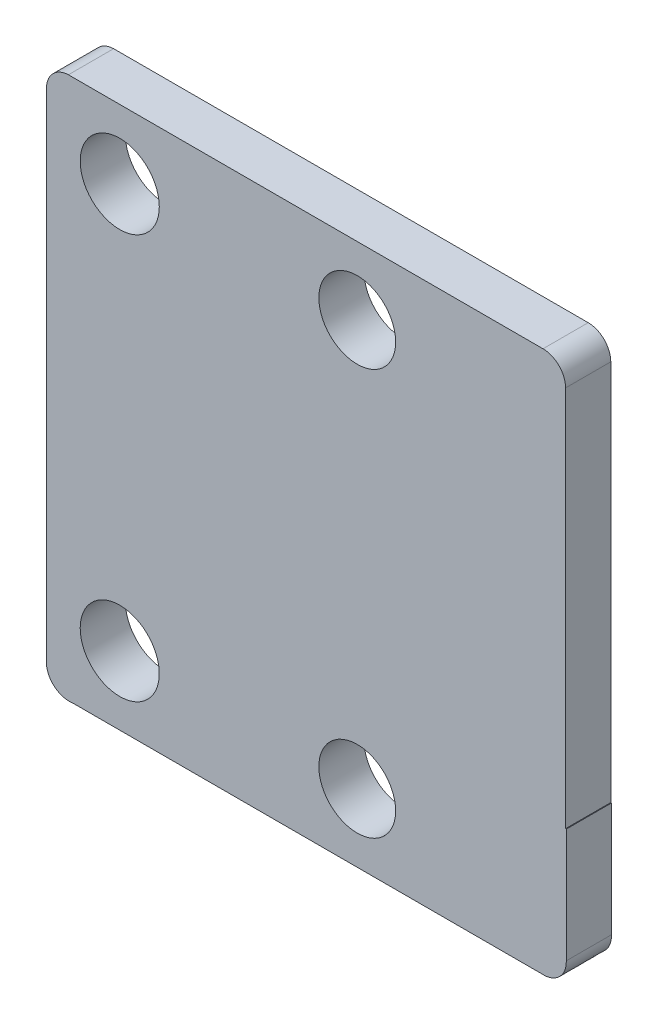
SolidWorks part; units mm, degrees
ref_plane "Front Plane" through (0, 0, 0) normal (0, 0, 1) x (1, 0, 0)
ref_plane "Top Plane" through (0, 0, 0) normal (0, 1, 0) x (1, 0, 0)
ref_plane "Right Plane" through (0, 0, 0) normal (1, 0, 0) x (0, 0, -1)
sketch "Sketch1" plane through (0, 0, 0) normal (0, 0, 1) x (1, 0, 0)
  line L8 (4.1311, 75.9014) -> (25.0323, 75.9014)
  line L9 (26, 76.9423) -> (26, 81.992)
  line L10 (26, 81.992) -> (25.9696, 81.992)
  line L11 (3, 81.9885) -> (3, 76.7619)
  line L12 (24.9696, 99.8823) -> (3.9696, 99.8823)
  line L13 (3, 98.8828) -> (3, 81.9885)
  line L15 (25.9696, 81.992) -> (25.9696, 98.8823)
  line L16 (3, 96.3357) -> (4, 96.3357) construction
  line L18 (3, 87.8886) -> (5.238, 87.8886) construction
  circle A0 centre (6.2405, 78.9415) radius 1.75
  arc A2 (25.9696, 98.8823) -> (24.9696, 99.8823) centre (24.9696, 98.8823) ccw
  arc A3 (3.9696, 99.8823) -> (3, 98.8828) centre (4, 98.8828) ccw
  circle A6 centre (16.75, 78.9116) radius 1.7
  circle A7 centre (16.75, 96.8774) radius 1.7
  circle A8 centre (6.2405, 96.8357) radius 1.75
  spline S2 degree 3 poles (3, 76.7619) (3.0185, 76.6305) (3.0629, 76.5036) (3.1948, 76.2776) (3.2839, 76.1765) (3.4921, 76.0174) (3.6125, 75.9581) (3.867, 75.891) (3.9997, 75.8829) (4.1311, 75.9014) knots 0 0 0 0 0.25 0.25 0.5 0.5 0.75 0.75 1 1 1 1
  spline S3 degree 3 poles (25.0323, 75.9014) (25.2977, 75.9098) (25.5537, 76.0289) (25.8207, 76.3177) (25.8908, 76.4318) (25.9826, 76.6788) (26.0042, 76.8097) (26, 76.9423) knots 0 0 0 0 0.5 0.5 0.75 0.75 1 1 1 1
  dimension "D2" = 3.5
  dimension "D1" = 16.8942
  dimension "D3" = 0.5
  dimension "D4" = 16.8903
  dimension "D5" = 21
extrude "Boss-Extrude1" add sketch "Sketch1" along normal blind 2
